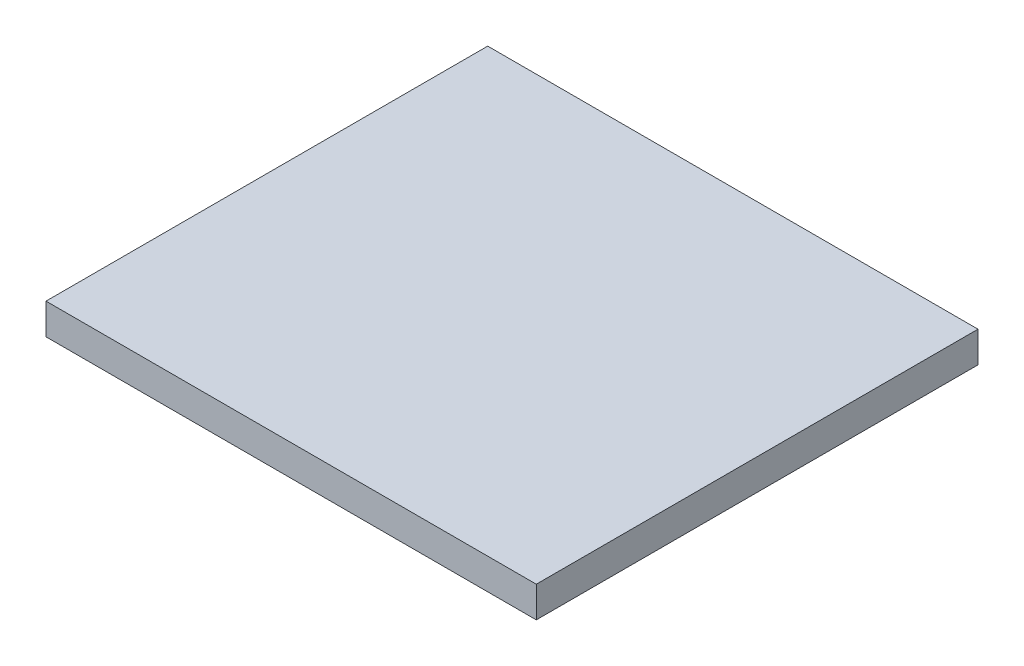
SolidWorks part; units mm, degrees
ref_plane "Front Plane" through (0, 0, 0) normal (0, 0, 1) x (1, 0, 0)
ref_plane "Top Plane" through (0, 0, 0) normal (0, 1, 0) x (1, 0, 0)
ref_plane "Right Plane" through (0, 0, 0) normal (1, 0, 0) x (0, 0, -1)
sketch "Sketch1" plane through (0, 0, 0) normal (0, 1, 0) x (1, 0, 0)
  line L1 (-80.9756, 49.0244) -> (30.0244, 49.0244)
  line L2 (-80.9756, 49.0244) -> (-80.9756, -50.9756)
  line L3 (-80.9756, -50.9756) -> (30.0244, -50.9756)
  line L4 (30.0244, 49.0244) -> (30.0244, -50.9756)
  dimension "D1" = 100
  dimension "D2" = 111
extrude "Boss-Extrude1" add sketch "Sketch1" along normal blind 7
